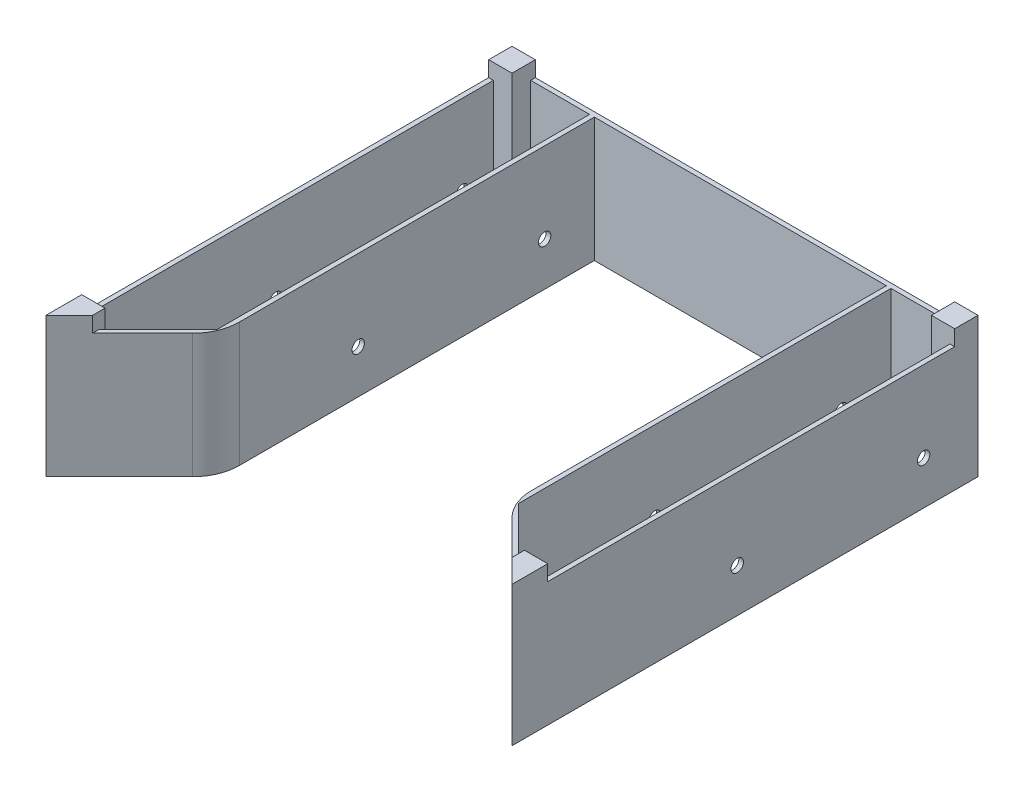
SolidWorks part; units mm, degrees
ref_plane "Front Plane" through (0, 0, 0) normal (0, 0, 1) x (1, 0, 0)
ref_plane "Top Plane" through (0, 0, 0) normal (0, 1, 0) x (1, 0, 0)
ref_plane "Right Plane" through (0, 0, 0) normal (1, 0, 0) x (0, 0, -1)
sketch "Sketch1" plane through (0, 0, 0) normal (0, 1, 0) x (1, 0, 0)
  line L0 (0, 184.6644) -> (0, -150) construction
  line L1 (-150, 150) -> (150, 150)
  line L2 (-150, 150) -> (-150, -150)
  line L4 (150, 150) -> (150, -150)
  line L5 (-150, 150) -> (0, 0) construction
  line L6 (-150, -150) -> (150, 150) construction
  line L7 (-147, 147) -> (-97, 147)
  line L8 (-147, 147) -> (-147, -142.7574)
  line L10 (-97, 147) -> (-97, -92.7574)
  line L16 (147, 147) -> (147, -142.7574)
  line L17 (147, 147) -> (97, 147)
  line L18 (97, 147) -> (97, -92.7574)
  line L20 (-94, 147) -> (94, 147)
  line L21 (-94, 147) -> (-94, -94)
  line L23 (94, 147) -> (94, -94)
  line L27 (-150, -150) -> (-94, -94)
  line L28 (150, -150) -> (94, -94)
  line L29 (-147, -142.7574) -> (-97, -92.7574)
  line L30 (147, -142.7574) -> (97, -92.7574)
  line L31 (152.1213, -147.8787) -> (85.2054, -80.9627) construction
  line L32 (150, -150) -> (83.084, -83.084) construction
  line L33 (94, -94) -> (150, -150) construction
  point P0 (0, 0)
  dimension "D1" = 300
  dimension "D2" = 3
  dimension "50" = 50
  dimension "D3" = 3
  dimension "3" = 3
  dimension "D4" = 300
  dimension "D6" = 3
  dimension "D8" = 3
extrude "Boss-Extrude1" add sketch "Sketch1" along normal blind 80
sketch "Sketch2" plane through (0, 0, 0) normal (1, 0, 0) x (0, 0, -1)
  line L0 (150, 28) -> (-150, 28) construction
  line L2 (150, 80) -> (150, 0) construction
  line L5 (0, 80) -> (0, -8.045) construction
  line L6 (-150, 80) -> (150, 80) construction
  line L7 (-150, 0) -> (150, 0) construction
  circle A3 centre (115, 28) radius 4
  circle A4 centre (-5, 28) radius 4
  point P8 (0, 0)
  dimension "D1" = 28
  dimension "D5" = 8
  dimension "D8" = 120
  dimension "D9" = 8
  dimension "D6" = 35
extrude "Cut-Extrude1" cut sketch "Sketch2" against normal through all both and the other way through all
sketch "Sketch4" plane through (150, 0, 0) normal (1, 0, 0) x (0, 0, -1)
  circle A0 centre (-147.1354, 77.3591) radius 1.5
  dimension "D1" = 3
sketch "Sketch5" plane through (0, 0, 0) normal (0, 1, 0) x (1, 0, 0)
  line L0 (-150, 150) -> (-150, -150) construction
  line L1 (-150, -127) -> (-135, -127)
  line L2 (-150, -127) -> (-150, -140.4272)
  line L4 (-135, -127) -> (-135, -135)
  line L5 (-150, -150) -> (-94, -94) construction
  line L6 (-150, -140.4272) -> (-150, -150)
  line L7 (-150, -150) -> (-135, -135)
  line L8 (0, 0) -> (0, -201.0806) construction
  line L9 (150, -150) -> (135, -135)
  line L10 (150, -140.4272) -> (150, -150)
  line L11 (135, -127) -> (135, -135)
  line L12 (150, -127) -> (150, -140.4272)
  line L13 (150, -127) -> (135, -127)
  line L14 (135, 150) -> (135, 135)
  line L15 (-150, 150) -> (-135, 150)
  line L16 (-150, 150) -> (-150, 135)
  line L17 (-150, 135) -> (-135, 135)
  line L18 (-135, 150) -> (-135, 135)
  line L19 (150, 135) -> (135, 135)
  line L20 (150, 150) -> (150, 135)
  line L21 (150, 150) -> (135, 150)
  dimension "D1" = 15
  dimension "D2" = 15
  dimension "D3" = 15
  dimension "D4" = 8
extrude "Boss-Extrude2" add sketch "Sketch5" along normal blind 90
fillet "Fillet1" radius 30 2 edges at (94, 40, 94) (-94, 40, 94)
